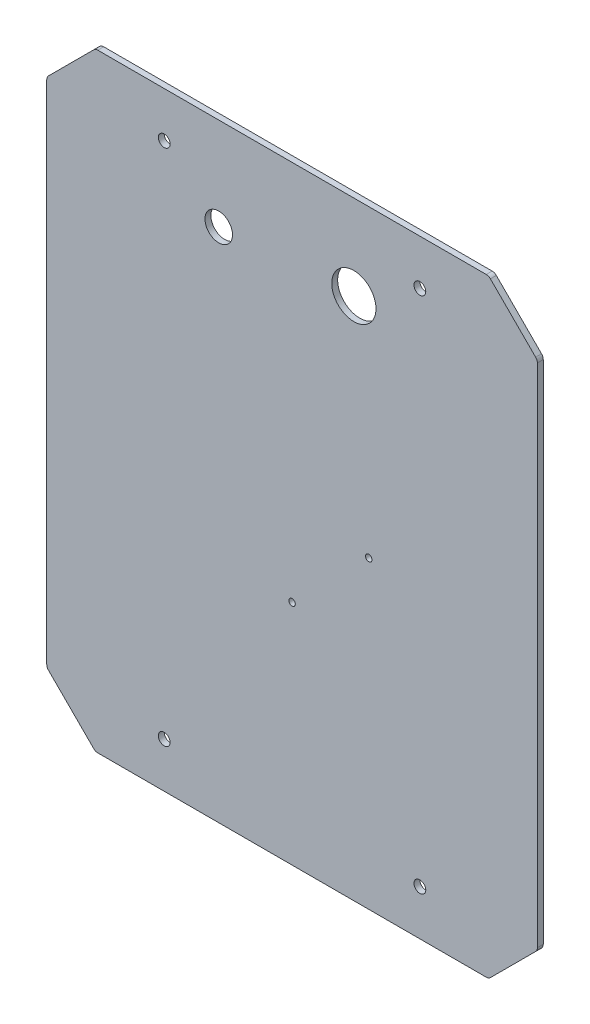
SolidWorks part; units mm, degrees
material "Alliage 1060"
ref_plane "Plan de dessus" through (0, 0, 0) normal (0, 0, 1) x (1, 0, 0)
ref_plane "Plan de droite" through (0, 0, 0) normal (0, 1, 0) x (1, 0, 0)
ref_plane "Plan de face" through (0, 0, 0) normal (1, 0, 0) x (0, 0, -1)
sketch "Esquisse1" plane through (0, 0, 0) normal (0, 0, 1) x (1, 0, 0)
  line L0 (0, 0) -> (-200, 0)
  line L1 (-200, 0) -> (-224.7487, 24.7487)
  line L2 (-224.7487, 24.7487) -> (-224.7487, 284.7487)
  line L3 (-224.7487, 284.7487) -> (-200, 309.4975)
  line L4 (-200, 309.4975) -> (0, 309.4975)
  line L5 (0, 309.4975) -> (24.7487, 284.7487)
  line L6 (24.7487, 284.7487) -> (24.7487, 24.7487)
  line L7 (24.7487, 24.7487) -> (0, 0)
  dimension "D1" = 260
  dimension "D2" = 35
  dimension "D3" = 135
  dimension "D4" = 200
extrude "Base" add sketch "Esquisse1" along normal blind 3
fillet "Congé1" radius 3 8 edges at (-200, 0, 1.5) (-224.7487, 24.7487, 1.5) (-224.7487, 284.7487, 1.5) (-200, 309.4975, 1.5) (0, 309.4975, 1.5) (24.7487, 284.7487, 1.5) (24.7487, 24.7487, 1.5) (0, 0, 1.5)
sketch "Esquisse19" plane through (0, 0, 0) normal (0, 0, -1) x (-1, 0, 0)
  line L0 (100, 309.4975) -> (100, 0) construction
  line L1 (1.2426, 309.4975) -> (198.7574, 309.4975) construction
  line L2 (198.7574, 0) -> (1.2426, 0) construction
  line L3 (-24.7487, 154.7487) -> (224.7487, 154.7487) construction
  line L4 (-24.7487, 25.9914) -> (-24.7487, 283.5061) construction
  line L5 (224.7487, 283.5061) -> (224.7487, 25.9914) construction
sketch "Esquisse20" plane through (0, 0, 0) normal (0, 0, -1) x (-1, 0, 0)
  line L0 (35, 286.4975) -> (35, 309.4975) construction
  line L1 (1.2426, 309.4975) -> (198.7574, 309.4975) construction
  line L2 (35, 286.4975) -> (100, 286.4975) construction
  line L3 (100, 309.4975) -> (100, 0) construction
  line L4 (100, 309.4975) -> (100, 0) construction
  line L5 (198.7574, 0) -> (1.2426, 0) construction
  line L6 (-24.7487, 154.7487) -> (224.7487, 154.7487) construction
  line L7 (-24.7487, 25.9914) -> (-24.7487, 283.5061) construction
  circle A0 centre (35, 286.4975) radius 3
  circle A1 centre (165, 286.4975) radius 3
  circle A2 centre (165, 23) radius 3
  circle A3 centre (35, 23) radius 3
  dimension "D3" = 6
  dimension "D1" = 65
  dimension "D2" = 23
extrude "Percage Profilés" cut sketch "Esquisse20" against normal through all
sketch "Esquisse21" plane through (0, 0, 0) normal (0, 0, -1) x (-1, 0, 0)
  line L1 (100, 154.7487) -> (100, 115.7487) construction
  line L2 (100, 309.4975) -> (100, 0) construction
  line L3 (100, 154.7487) -> (61, 154.7487) construction
  line L4 (-24.7487, 154.7487) -> (224.7487, 154.7487) construction
  circle A1 centre (61, 154.7487) radius 1.65
  circle A2 centre (100, 115.7487) radius 1.65
  dimension "D2" = 3.3
  dimension "D1" = 39
extrude "Percage Lidar" cut sketch "Esquisse21" against normal through all
sketch "Esquisse22" plane through (0, 0, 0) normal (0, 0, -1) x (-1, 0, 0)
  circle A0 centre (68.56, 266.3171) radius 11.25
  dimension "D1" = 22.5
extrude "Enlèv. mat.-Extru.3" cut sketch "Esquisse22" against normal through all
sketch "Esquisse23" plane through (0, 0, 0) normal (0, 0, -1) x (-1, 0, 0)
  circle A0 centre (137.2823, 262.4065) radius 7
  dimension "D1" = 14
extrude "Enlèv. mat.-Extru.4" cut sketch "Esquisse23" against normal through all
